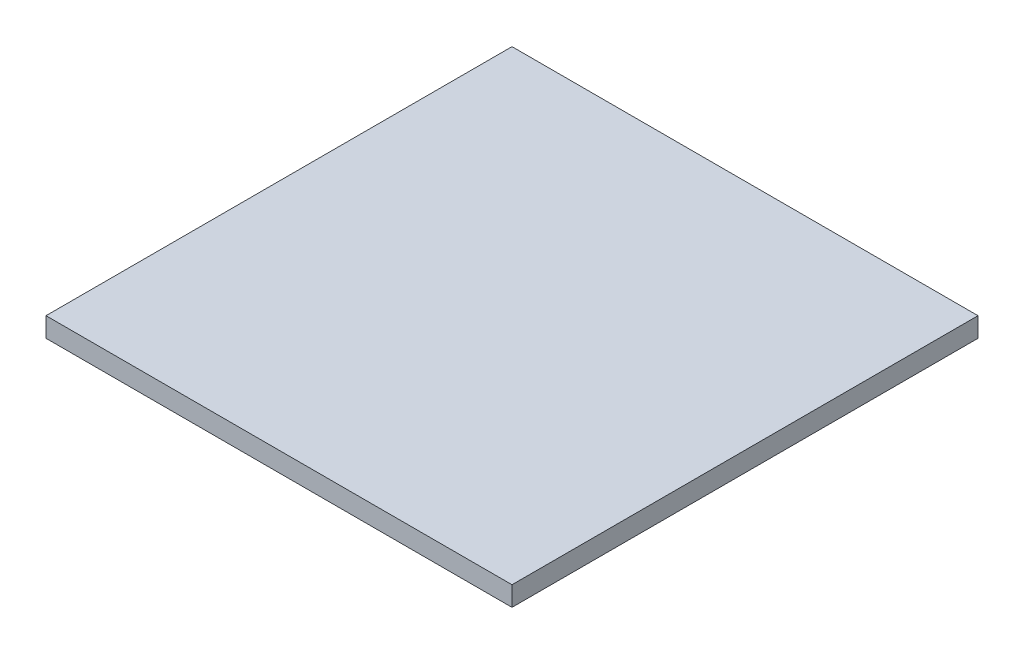
SolidWorks part; units mm, degrees
material "Cast Alloy Steel"
ref_plane "Front Plane" through (0, 0, 0) normal (0, 0, 1) x (1, 0, 0)
ref_plane "Top Plane" through (0, 0, 0) normal (0, 1, 0) x (1, 0, 0)
ref_plane "Right Plane" through (0, 0, 0) normal (1, 0, 0) x (0, 0, -1)
sketch "Sketch1" plane through (0, 0, 0) normal (0, 1, 0) x (1, 0, 0)
  line L0 (-2, 254.0804) -> (-2, -149.9196)
  line L1 (0, 252.0804) -> (400, 252.0804)
  line L2 (0, 252.0804) -> (0, -147.9196)
  line L3 (0, -147.9196) -> (400, -147.9196)
  line L4 (400, 252.0804) -> (400, -147.9196)
  line L5 (-2, -149.9196) -> (402, -149.9196)
  line L6 (402, 254.0804) -> (402, -149.9196)
  line L7 (-2, 254.0804) -> (402, 254.0804)
  dimension "D1" = 400
  dimension "D2" = 400
  dimension "D3" = 2
extrude "Boss-Extrude1" add sketch "Sketch1" along normal blind 15
ref_plane "Plane1" through (-2, 15, 149.9196) normal (1, 0, 0) x (0, 0, -1)
sketch "Sketch3" plane through (0, 15, 0) normal (0, 1, 0) x (1, 0, 0)
  line L1 (-2, 254.0804) -> (402, 254.0804)
  line L2 (-2, 254.0804) -> (-2, -149.9196)
  line L3 (-2, -149.9196) -> (402, -149.9196)
  line L4 (402, 254.0804) -> (402, -149.9196)
extrude "Boss-Extrude2" add sketch "Sketch3" along normal blind 2
sketch "Sketch4" plane through (0, 17, 0) normal (0, 1, 0) x (1, 0, 0)
  line L0 (200, 254.0804) -> (200, -149.9196) construction
  line L1 (402, 254.0804) -> (-2, 254.0804) construction
  line L2 (-2, -149.9196) -> (402, -149.9196) construction
  circle A0 centre (77, -70.9196) radius 4
